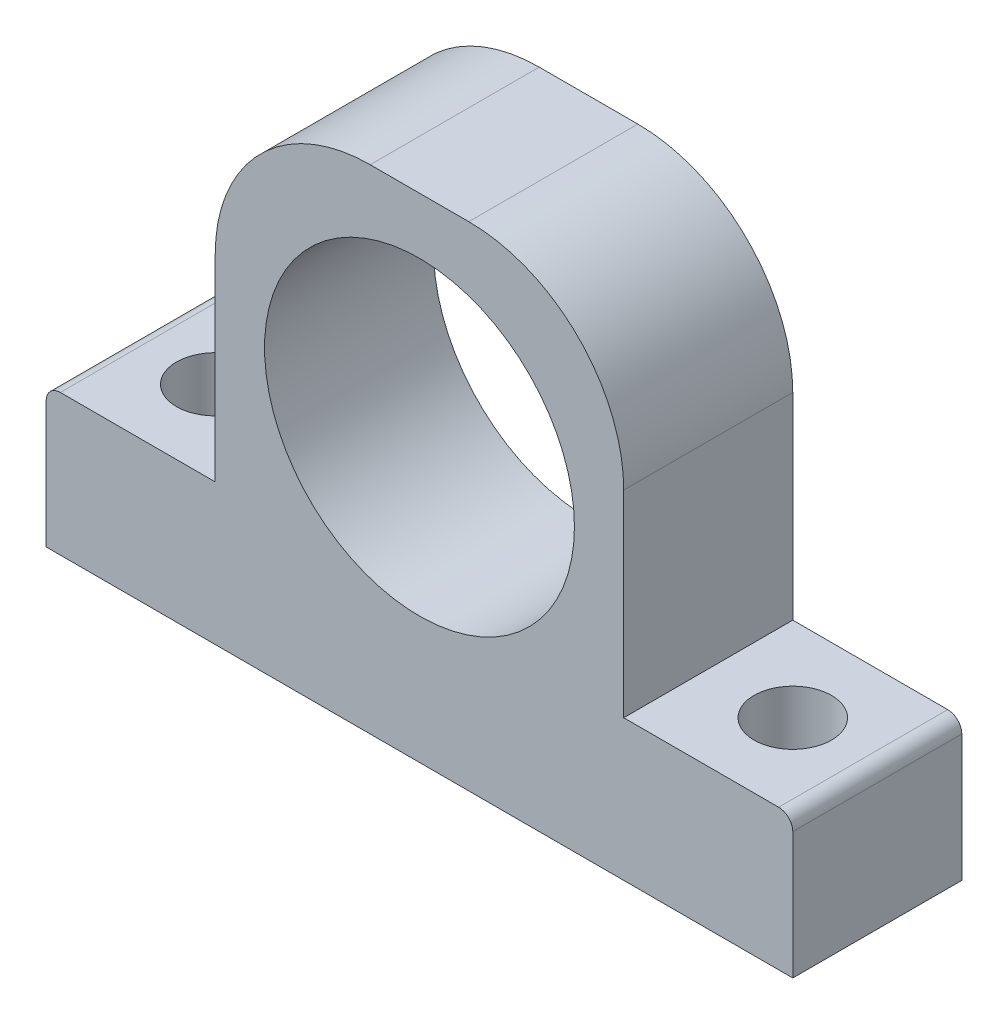
SolidWorks part; units mm, degrees
ref_plane "前视基准面" through (0, 0, 0) normal (0, 0, 1) x (1, 0, 0)
ref_plane "上视基准面" through (0, 0, 0) normal (0, 1, 0) x (1, 0, 0)
ref_plane "右视基准面" through (0, 0, 0) normal (1, 0, 0) x (0, 0, -1)
other "Configuration Table"
sketch "草图1" plane through (0, 0, 0) normal (0, 0, 1) x (1, 0, 0)
  line L0 (14.5, 10) -> (25.5, 10)
  line L1 (-25.5, 10) -> (-14.5, 10)
  line L2 (-26.5, 9) -> (-26.5, 0)
  line L3 (-26.5, 0) -> (26.5, 0)
  line L4 (26.5, 9) -> (26.5, 0)
  line L5 (-3.5, 35) -> (3.5, 35)
  line L6 (-14.5, 24) -> (-14.5, 10)
  line L8 (14.5, 24) -> (14.5, 10)
  circle A0 centre (0, 20) radius 11
  arc A1 (-3.5, 35) -> (-14.5, 24) centre (-3.5, 24) ccw
  arc A2 (3.5, 35) -> (14.5, 24) centre (3.5, 24) cw
  arc A3 (25.5, 10) -> (26.5, 9) centre (25.5, 9) cw
  arc A4 (-25.5, 10) -> (-26.5, 9) centre (-25.5, 9) ccw
  point P10 (0, 0)
  point P11 (0, 0)
  point P13 (0, 0)
  point P14 (0, 0)
  point P15 (0, 0)
  point P16 (0, 0)
  point P19 (-14.5, 35)
  point P22 (14.5, 35)
  point P27 (-26.5, 10)
  dimension "D5" = 22
  dimension "D7" = 11
  dimension "D8" = 11
  dimension "D9" = 1
  dimension "D1" = 10
  dimension "D2" = 53
  dimension "D3" = 29
  dimension "D4" = 35
  dimension "D6" = 20
extrude "凸台-拉伸1" add sketch "草图1" along normal blind 12
sketch "草图2" plane through (0, 10, 0) normal (0, 1, 0) x (1, 0, 0)
  line L0 (-25.5, -12) -> (-25.5, 0) construction
  line L1 (3.5, -12) -> (-3.5, -12) construction
  line L2 (0, -12) -> (0, 0) construction
  circle A0 centre (-20.5, -6) radius 2.75
  circle A1 centre (20.5, -6) radius 2.75
  point P6 (-25.5, -6)
  point P10 (0, -12)
  dimension "D1" = 5.5
  dimension "D2" = 41
extrude "切除-拉伸1" cut sketch "草图2" against normal through all
